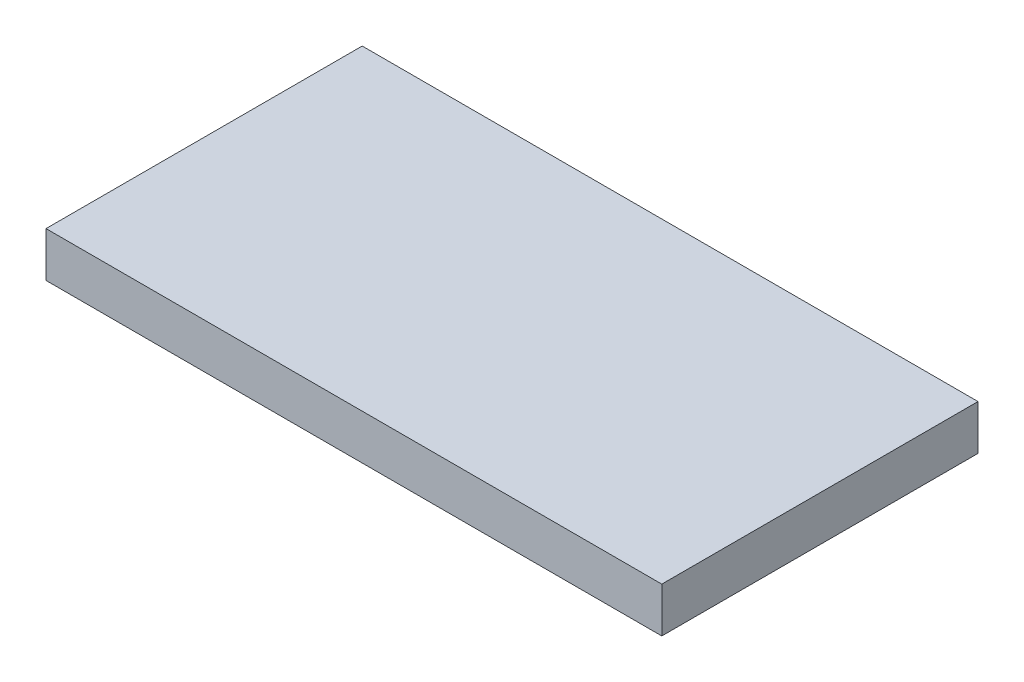
SolidWorks part; units mm, degrees
material "Oak"
ref_plane "Front Plane" through (0, 0, 0) normal (0, 0, 1) x (1, 0, 0)
ref_plane "Top Plane" through (0, 0, 0) normal (0, 1, 0) x (1, 0, 0)
ref_plane "Right Plane" through (0, 0, 0) normal (1, 0, 0) x (0, 0, -1)
sketch "Sketch1" plane through (0, 0, 0) normal (0, 1, 0) x (1, 0, 0)
  line L1 (0, 0) -> (370, 0)
  line L2 (0, 0) -> (0, -190)
  line L3 (0, -190) -> (370, -190)
  line L4 (370, 0) -> (370, -190)
  dimension "D1" = 370
  dimension "D2" = 190
extrude "Boss-Extrude1" add sketch "Sketch1" along normal blind 27
